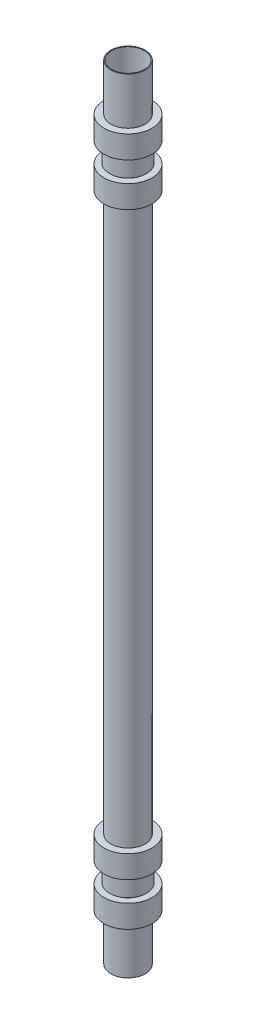
SolidWorks part; units mm, degrees
ref_plane "Plano frontal" through (0, 0, 0) normal (0, 0, 1) x (1, 0, 0)
ref_plane "Plano superior" through (0, 0, 0) normal (0, 1, 0) x (1, 0, 0)
ref_plane "Plano direito" through (0, 0, 0) normal (1, 0, 0) x (0, 0, -1)
sketch "Esboço1" plane through (0, 0, 0) normal (0, 0, 1) x (1, 0, 0)
  line L0 (0, 0) -> (0, 1633) construction
  line L1 (0, 1633) -> (-35.8382, 1633)
  line L2 (-35.8382, 1633) -> (-35.8382, 1534.9932)
  line L3 (-35.8382, 1534.9932) -> (-50.2455, 1534.9932)
  line L4 (-50.2455, 1398.1162) -> (-35.8382, 1398.1162)
  line L5 (0, 0) -> (0, 1633)
  line L6 (-35.8382, 234.69) -> (-50.2455, 234.69)
  line L7 (-50.2455, 234.69) -> (-50.2455, 98.01)
  line L8 (-50.2455, 1534.9932) -> (-50.2455, 1398.1162)
  line L9 (-35.8382, 1398.1162) -> (-35.8382, 234.69)
  line L10 (-35.8382, 0) -> (0, 0)
  line L11 (-50.2455, 98.01) -> (-35.8382, 98.01)
  line L12 (-35.8382, 98.01) -> (-35.8382, 0)
  dimension "D1" = 1633
  dimension "D2" = 136.68
  dimension "D3" = 98.01
  dimension "D4" = 98.0068
revolve "Revolução6" add sketch "Esboço1" angle 360 about L0
sketch "Esboço3" plane through (0, 0, 0) normal (1, 0, 0) x (0, 0, -1)
  line L0 (36.5588, 1487.8221) -> (50.2455, 1487.8221)
  line L1 (50.2455, 1398.1162) -> (50.2455, 1534.9932) construction
  line L2 (50.2455, 1487.8221) -> (50.2455, 1445.2862)
  line L3 (50.2455, 1445.2862) -> (36.5588, 1445.2862)
  line L5 (0, 1534.9932) -> (0, 1398.1162) construction
  line L6 (50.2455, 1534.9932) -> (-50.2455, 1534.9932) construction
  line L7 (-35.8382, 1398.1162) -> (35.8382, 1398.1162) construction
  line L8 (36.5588, 1487.8221) -> (36.5588, 1445.2862)
  line L9 (-50.2455, 1398.1162) -> (50.2455, 1398.1162) construction
  dimension "D1" = 47.1711
  dimension "D2" = 47.17
  dimension "D3" = 13.6868
revolve "Corte-Revolução2" cut sketch "Esboço3" angle 360 about L5
sketch "Esboço4" plane through (0, 0, 0) normal (1, 0, 0) x (0, 0, -1)
  line L0 (0, 1487.8221) -> (0, 1445.2862) construction
  line L1 (-36.5588, 1487.8221) -> (36.5588, 1487.8221) construction
  line L2 (50.2455, 1445.2862) -> (-50.2455, 1445.2862) construction
  line L3 (0, 1485.8221) -> (38.6809, 1485.8221)
  line L4 (38.6809, 1485.8221) -> (38.6809, 1447.2862)
  line L5 (38.6809, 1447.2862) -> (0, 1447.2862)
  line L6 (0, 1485.8221) -> (0, 1447.2862)
  dimension "D1" = 2
  dimension "D2" = 2
  dimension "D3" = 38.6809
revolve "Revolução7" add sketch "Esboço4" angle 360 about L0
sketch "Esboço6" plane through (0, 1633, 0) normal (0, 1, 0) x (1, 0, 0)
  circle A0 centre (0, 0) radius 34.062
extrude "Corte-extrusão1" cut sketch "Esboço6" against normal through all both and the other way through all
sketch "Esboço7" plane through (0, 0, 0) normal (1, 0, 0) x (0, 0, -1)
  line L0 (0, 234.69) -> (0, 98.01) construction
  line L1 (50.2455, 234.69) -> (-50.2455, 234.69) construction
  line L2 (-35.8382, 98.01) -> (35.8382, 98.01) construction
  line L3 (50.2455, 187.72) -> (36.5555, 187.72)
  line L4 (50.2455, 98.01) -> (50.2455, 234.69) construction
  line L5 (50.2455, 187.72) -> (50.2455, 145.18)
  line L6 (36.5555, 187.72) -> (36.5555, 145.18)
  line L7 (36.5555, 145.18) -> (50.2455, 145.18)
  dimension "D1" = 47.17
  dimension "D2" = 42.54
  dimension "D3" = 13.69
revolve "Corte-Revolução3" cut sketch "Esboço7" angle 360 about L0
sketch "Esboço8" plane through (0, 0, 0) normal (0, 0, 1) x (1, 0, 0)
  line L0 (0, 145.18) -> (0, 187.72) construction
  line L1 (50.2455, 145.18) -> (-50.2455, 145.18) construction
  line L2 (-36.5555, 187.72) -> (36.5555, 187.72) construction
  line L3 (0, 185.72) -> (38.68, 185.72)
  line L4 (38.68, 185.72) -> (38.68, 147.18)
  line L5 (38.68, 147.18) -> (0, 147.18)
  line L6 (0, 185.72) -> (0, 147.18)
  dimension "D1" = 38.68
  dimension "D2" = 2
  dimension "D3" = 2
revolve "Revolução8" add sketch "Esboço8" angle 360 about L0
